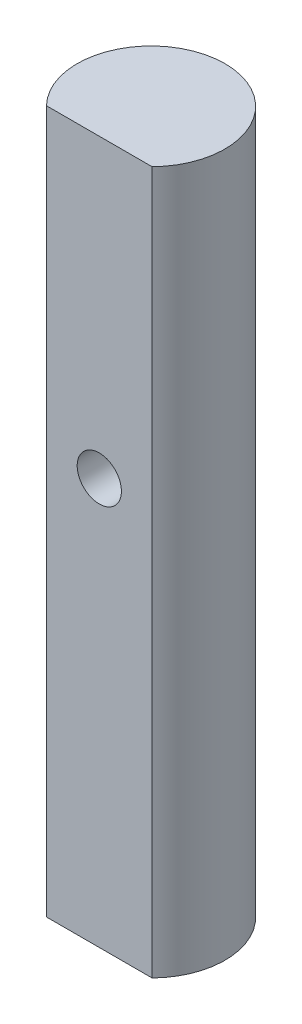
SolidWorks part; units mm, degrees
material "O-1 GS"
ref_plane "Z" through (0, 0, 0) normal (0, 0, 1) x (1, 0, 0)
ref_plane "Y" through (0, 0, 0) normal (0, 1, 0) x (1, 0, 0)
ref_plane "X" through (0, 0, 0) normal (1, 0, 0) x (0, 0, -1)
sketch "Sketch1" plane through (0, 0, 0) normal (0, 1, 0) x (1, 0, 0)
  circle A0 centre (0, 0) radius 6.35
  dimension "D1" = 12.7
extrude "Boss-Extrude1" add sketch "Sketch1" along normal blind 60.3249
sketch "Sketch2" plane through (0, 60.3249, 0) normal (0, 1, 0) x (1, 0, 0)
  line L0 (0, -6.35) -> (0, -4.445) construction
  line L1 (0, -4.445) -> (-5.6552, -4.445)
  line L2 (-5.6552, -4.445) -> (-5.6552, -6.8505)
  line L3 (-5.6552, -6.8505) -> (5.9079, -6.8505)
  line L4 (5.9079, -6.8505) -> (5.9079, -4.445)
  line L5 (5.9079, -4.445) -> (0, -4.445)
  circle A0 centre (0, 0) radius 6.35 construction
  dimension "D1" = 1.905
extrude "Cut-Extrude1" cut sketch "Sketch2" against normal through all
hole_wizard "#10-24 Tapped Hole1" positions "Sketch3" profile "Sketch4" tap size "#10-24" standard "ANSI Inch" end condition through all
sketch "Sketch3" plane through (0, 0, 4.445) normal (0, 0, 1) x (1, 0, 0)
  line L0 (4.5348, 0) -> (-4.5348, 0) construction
  point P0 (0, 34.8781)
  dimension "D1" = 34.8781
sketch "Sketch4" plane through (0, 34.8781, 4.445) normal (1, 0, 0) x (0, -1, 0)
  line L0 (0, 0) -> (0, 10.795)
  line L1 (0, 10.795) -> (1.8986, 10.795)
  line L2 (1.8986, 10.795) -> (1.8986, 0)
  line L5 (1.8986, 0) -> (0, 0)
  line L11 (0, -6.35) -> (0, 107.95) construction
  dimension "Thru Tap Drill Dia." = 3.7973
  dimension "Thru Tap Drill Depth" = 10.795
cosmetic thread "Hole Thread1" parameters "D2"=4.826
